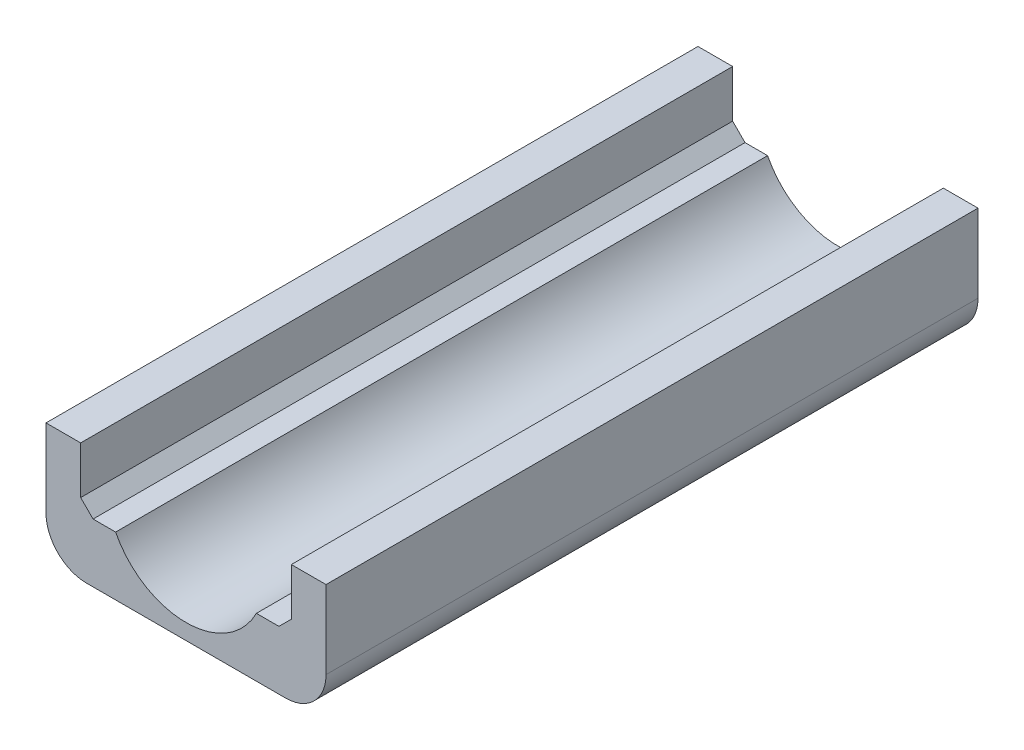
SolidWorks part; units mm, degrees
ref_plane "Front Plane" through (0, 0, 0) normal (0, 0, 1) x (1, 0, 0)
ref_plane "Top Plane" through (0, 0, 0) normal (0, 1, 0) x (1, 0, 0)
ref_plane "Right Plane" through (0, 0, 0) normal (1, 0, 0) x (0, 0, -1)
sketch "Sketch1" plane through (0, 0, 0) normal (0, 0, 1) x (1, 0, 0)
  line L3 (-22.4964, 29.27) -> (-22.4964, 10)
  line L4 (-22.4964, 29.27) -> (-13.9364, 29.27)
  line L9 (-13.9364, 29.27) -> (-13.9364, 17.58)
  line L10 (-13.9364, 17.58) -> (-10.8746, 14.5182)
  line L11 (-10.8746, 14.5182) -> (-5.3046, 14.5182)
  line L12 (-12.4964, 0) -> (36.6487, 0)
  line L14 (46.6487, 29.27) -> (46.6487, 10)
  line L16 (-5.3046, 14.5182) -> (5.4996, 14.5182) construction
  line L17 (46.6487, 29.27) -> (38.0887, 29.27)
  line L18 (38.0887, 29.27) -> (38.0887, 17.58)
  line L19 (38.0887, 17.58) -> (35.027, 14.5182)
  line L20 (35.027, 14.5182) -> (29.457, 14.5182)
  arc A2 (-12.4964, 0) -> (-22.4964, 10) centre (-12.4964, 10) cw
  arc A4 (36.6487, 0) -> (46.6487, 10) centre (36.6487, 10) ccw
  arc A5 (-5.3046, 14.5182) -> (29.457, 14.5182) centre (12.0762, 23.3589) ccw
  point P9 (-22.4964, 0)
  point P12 (35.9136, 0)
  dimension "D3" = 8.56
  dimension "D6" = 10
  dimension "D1" = 58.41
  dimension "D2" = 29.27
  dimension "D8" = 11.69
  dimension "D9" = 11.69
  dimension "D10" = 4.33
  dimension "D11" = 135
  dimension "D12" = 5.57
  dimension "D15" = 19.5
extrude "Boss-Extrude1" add sketch "Sketch1" along normal blind 161
